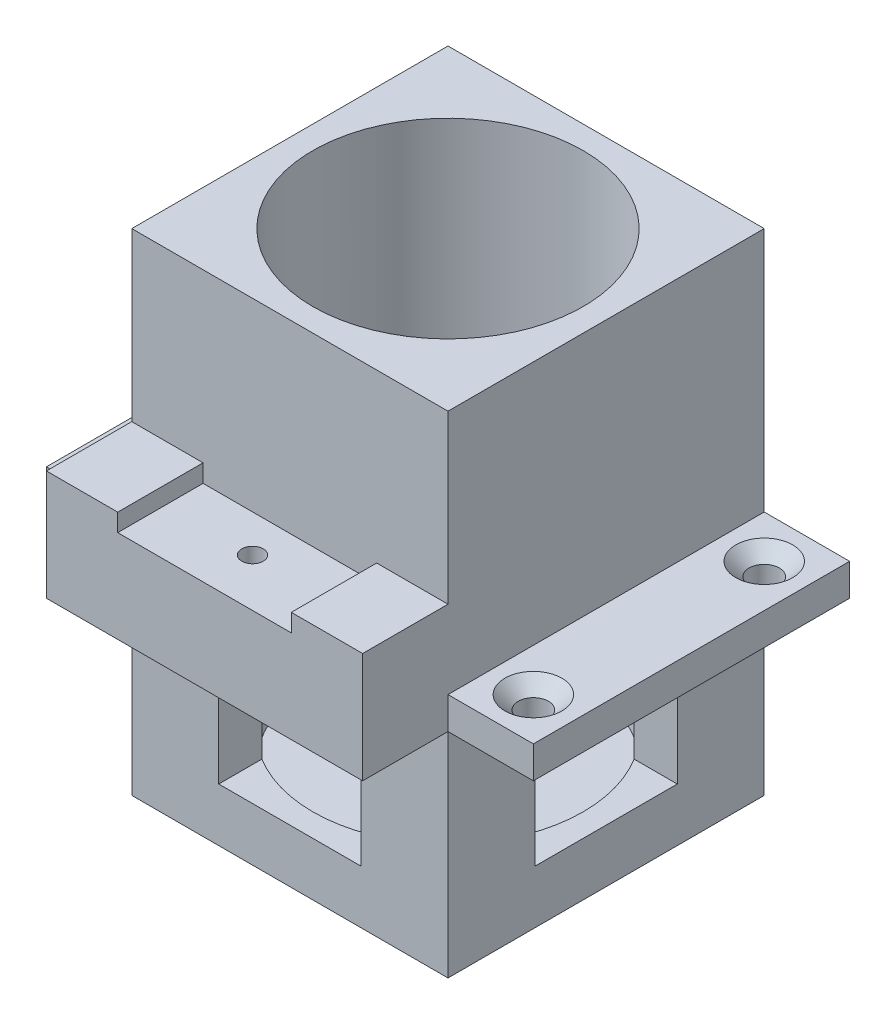
SolidWorks part; units mm, degrees
ref_plane "Front Plane" through (0, 0, 0) normal (0, 0, 1) x (1, 0, 0)
ref_plane "Top Plane" through (0, 0, 0) normal (0, 1, 0) x (1, 0, 0)
ref_plane "Right Plane" through (0, 0, 0) normal (1, 0, 0) x (0, 0, -1)
sketch "Sketch1" plane through (0, 0, 0) normal (0, 1, 0) x (1, 0, 0)
  line L1 (-22.225, -22.225) -> (22.225, -22.225)
  line L2 (-22.225, -22.225) -> (-22.225, 22.225)
  line L3 (-22.225, 22.225) -> (22.225, 22.225)
  line L4 (22.225, -22.225) -> (22.225, 22.225)
  line L5 (-22.225, -22.225) -> (22.225, 22.225) construction
  line L6 (-22.225, 22.225) -> (22.225, -22.225) construction
  point P0 (0, 0)
extrude "Boss-Extrude1" add sketch "Sketch1" along normal blind 90
sketch "Sketch2" plane through (0, 90, 0) normal (0, 1, 0) x (1, 0, 0)
  circle A0 centre (0, 0) radius 19
extrude "Cut-Extrude1" cut sketch "Sketch2" against normal blind 45
sketch "Sketch3" plane through (0, 45, 0) normal (0, 1, 0) x (1, 0, 0)
  circle A0 centre (0, 0) radius 19
extrude "Cut-Extrude2" cut sketch "Sketch3" against normal blind 41
sketch "Sketch4" plane through (0, 90, 0) normal (0, 1, 0) x (1, 0, 0)
  line L1 (-22.225, -22.225) -> (22.225, -22.225)
  line L2 (-22.225, -22.225) -> (-22.225, 22.225)
  line L3 (-22.225, 22.225) -> (22.225, 22.225)
  line L4 (22.225, -22.225) -> (22.225, 22.225)
  line L5 (-22.225, -22.225) -> (22.225, 22.225) construction
  line L6 (-22.225, 22.225) -> (22.225, -22.225) construction
  point P0 (0, 0)
extrude "Cut-Extrude3" cut sketch "Sketch4" against normal blind 21
sketch "Sketch6" plane through (0, 0, 22.225) normal (0, 0, 1) x (1, 0, 0)
  line L0 (0, 0) -> (0, 15) construction
  line L2 (-10, 7.5) -> (10, 7.5)
  line L3 (-10, 7.5) -> (-10, 22.5)
  line L4 (-10, 22.5) -> (10, 22.5)
  line L5 (10, 7.5) -> (10, 22.5)
  line L6 (-10, 7.5) -> (10, 22.5) construction
  line L7 (-10, 22.5) -> (10, 7.5) construction
extrude "Cut-Extrude4" cut sketch "Sketch6" against normal through all contours L3 L2 L5 L4
sketch "Sketch8" plane through (-22.225, 0, 0) normal (-1, 0, 0) x (0, 0, 1)
  line L0 (0, 0) -> (0, 15) construction
  line L2 (-10, 7.5) -> (10, 7.5)
  line L3 (-10, 7.5) -> (-10, 22.5)
  line L4 (-10, 22.5) -> (10, 22.5)
  line L5 (10, 7.5) -> (10, 22.5)
  line L6 (-10, 7.5) -> (10, 22.5) construction
  line L7 (-10, 22.5) -> (10, 7.5) construction
extrude "Cut-Extrude5" cut sketch "Sketch8" against normal through all contours L3 L2 L5 L4
sketch "Sketch11" plane through (0, 0, 22.225) normal (0, 0, 1) x (1, 0, 0)
  line L0 (0, 0) -> (0, 28.5) construction
  line L1 (-22.225, 0) -> (22.225, 0) construction
  line L2 (-22.225, 28.5) -> (22.225, 28.5) construction
  line L3 (22.225, 69) -> (22.225, 0) construction
  line L4 (-22.225, 28.5) -> (-22.225, 15.8) construction
  line L5 (-22.225, 69) -> (-22.225, 0) construction
  line L7 (-22.225, 15.8) -> (22.225, 15.8) construction
  line L8 (-22.225, 15.8) -> (-22.225, 69)
  line L9 (-22.225, 69) -> (22.225, 69)
  line L10 (22.225, 15.8) -> (22.225, 69)
  line L11 (-22.225, 28.5) -> (22.225, 28.5)
  line L12 (-22.225, 28.5) -> (-22.225, 0)
  line L13 (-22.225, 0) -> (22.225, 0)
  line L14 (22.225, 28.5) -> (22.225, 0)
  point P9 (0, 28.5)
sketch "Sketch16" plane through (0, 0, 22.225) normal (0, 0, 1) x (1, 0, 0)
  line L0 (22.225, 15.8) -> (22.225, 69) construction
  line L1 (-22.225, 28.5) -> (22.225, 28.5)
  line L2 (-22.225, 28.5) -> (-22.225, 32.5)
  line L3 (-22.225, 32.5) -> (22.225, 32.5)
  line L4 (22.225, 28.5) -> (22.225, 32.5)
sketch "Sketch17" plane through (0, 0, 22.225) normal (0, 0, 1) x (1, 0, 0)
  line L0 (-22.225, 28.5) -> (-22.225, 30)
  line L1 (-22.225, 15.8) -> (-22.225, 69) construction
  line L2 (22.225, 15.8) -> (22.225, 69) construction
  line L3 (-22.225, 30) -> (22.225, 30)
  line L4 (-22.225, 30) -> (-22.225, 45.5)
  line L5 (-22.225, 45.5) -> (-12.2, 45.5)
  line L6 (22.225, 30) -> (22.225, 45.5)
  line L8 (-12.2, 45.5) -> (-12.2, 43)
  line L9 (12.2, 45.5) -> (22.225, 45.5)
  line L10 (-22.225, 43) -> (-22.225, 45.5)
  line L11 (12.2, 45.5) -> (12.2, 43)
  line L12 (-22.225, 43) -> (-22.225, 30)
  line L13 (22.225, 45.5) -> (22.225, 43)
  line L14 (-12.2, 43) -> (12.2, 43)
  line L15 (12.2, 45.5) -> (22.225, 45.5)
  line L16 (-22.225, 30) -> (22.225, 30)
  line L17 (-22.225, 30) -> (-22.225, 45.5)
  line L18 (-22.225, 45.5) -> (-12.2, 45.5)
  line L19 (22.225, 30) -> (22.225, 45.5)
  line L20 (-12.2, 43) -> (12.2, 43)
  line L21 (-12.2, 43) -> (-12.2, 45.5)
  line L23 (12.2, 43) -> (12.2, 45.5)
  point P13 (0, 45.5)
sketch "Sketch18" plane through (0, 0, 22.225) normal (0, 0, 1) x (1, 0, 0)
  line L0 (12.2, 45.5) -> (22.225, 45.5)
  line L1 (-22.225, 30) -> (22.225, 30)
  line L2 (-22.225, 30) -> (-22.225, 45.5)
  line L3 (-22.225, 45.5) -> (-12.2, 45.5)
  line L4 (22.225, 30) -> (22.225, 45.5)
  line L5 (-12.2, 43) -> (12.2, 43)
  line L6 (-12.2, 43) -> (-12.2, 45.5)
  line L8 (12.2, 43) -> (12.2, 45.5)
extrude "Boss-Extrude2" add sketch "Sketch18" along normal blind 12 contours L6 L3 L2 L1 L4 L0 L8 L5
sketch "Sketch19" plane through (0, 4, 0) normal (0, 1, 0) x (1, 0, 0)
  line L0 (0, 0) -> (0, -7) construction
  circle A0 centre (0, -7) radius 3
sketch "Sketch20" plane through (0, 43, 0) normal (0, 1, 0) x (1, 0, 0)
  line L0 (0, -22.225) -> (0, -27.475) construction
  circle A0 centre (0, -27.475) radius 1.51
extrude "Cut-Extrude6" cut sketch "Sketch20" against normal up to surface (13 mm away) up to face at (0, 30, 28.225)
sketch "Sketch21" plane through (-22.225, 0, 0) normal (-1, 0, 0) x (0, 0, 1)
  line L0 (-22.225, 69) -> (-22.225, 0) construction
  line L1 (22.225, 30) -> (-22.225, 30)
  line L2 (22.225, 30) -> (22.225, 34)
  line L3 (22.225, 34) -> (-22.225, 34)
  line L4 (-22.225, 30) -> (-22.225, 34)
extrude "Boss-Extrude4" add sketch "Sketch21" along normal blind 12 contours L2 L1 L4 L3
sketch "Sketch22" plane through (0, 34, 0) normal (0, 1, 0) x (1, 0, 0)
  line L0 (-34.225, 0) -> (-22.225, 0) construction
  line L1 (-34.225, -22.225) -> (-28.225, -22.225)
  line L2 (-34.225, -22.225) -> (-34.225, -16.225)
  line L3 (-34.225, -16.225) -> (-28.225, -16.225)
  line L4 (-28.225, -22.225) -> (-28.225, -16.225)
  line L5 (-34.225, -22.225) -> (-34.225, 22.225) construction
  line L6 (-22.225, -22.225) -> (-22.225, 22.225) construction
  line L7 (0, -31.0475) -> (0, 31.0475) construction
  circle A0 centre (-28.225, -16.225) radius 4
  circle A1 centre (-28.225, -16.225) radius 2.125
  circle A2 centre (-28.225, 16.225) radius 2.125
  circle A3 centre (-28.225, 16.225) radius 4
  circle A4 centre (28.225, -16.225) radius 4
  circle A5 centre (28.225, -16.225) radius 2.125
  circle A6 centre (28.225, 16.225) radius 2.125
  circle A7 centre (28.225, 16.225) radius 4
extrude "Cut-Extrude11" cut sketch "Sketch22" against normal blind 2 draft 45 contours A0 | A3 | A4 | A7
sketch "Sketch23" plane through (0, 34, 0) normal (0, 1, 0) x (1, 0, 0)
  circle A0 centre (-28.225, -16.225) radius 2
  circle A1 centre (-28.225, 16.225) radius 2
extrude "Cut-Extrude12" cut sketch "Sketch23" against normal blind 12
sketch "Sketch24" plane through (22.225, 0, 0) normal (1, 0, 0) x (0, 0, -1)
  line L0 (22.225, 69) -> (22.225, 0) construction
  line L1 (-22.225, 30) -> (22.225, 30)
  line L2 (-22.225, 30) -> (-22.225, 34.5)
  line L3 (-22.225, 34.5) -> (22.225, 34.5)
  line L4 (22.225, 30) -> (22.225, 34.5)
extrude "Boss-Extrude5" add sketch "Sketch24" along normal blind 12 contours L2 L1 L4 L3
sketch "Sketch25" plane through (0, 34.5, 0) normal (0, 1, 0) x (1, 0, 0)
  circle A0 centre (28.225, 16.225) radius 4
  circle A1 centre (28.225, -16.225) radius 4
extrude "Cut-Extrude13" cut sketch "Sketch25" against normal blind 2 draft 45
sketch "Sketch26" plane through (0, 34.5, 0) normal (0, 1, 0) x (1, 0, 0)
  circle A0 centre (28.225, 16.225) radius 2.125
  circle A1 centre (28.225, -16.225) radius 2.125
extrude "Cut-Extrude14" cut sketch "Sketch26" against normal blind 12
